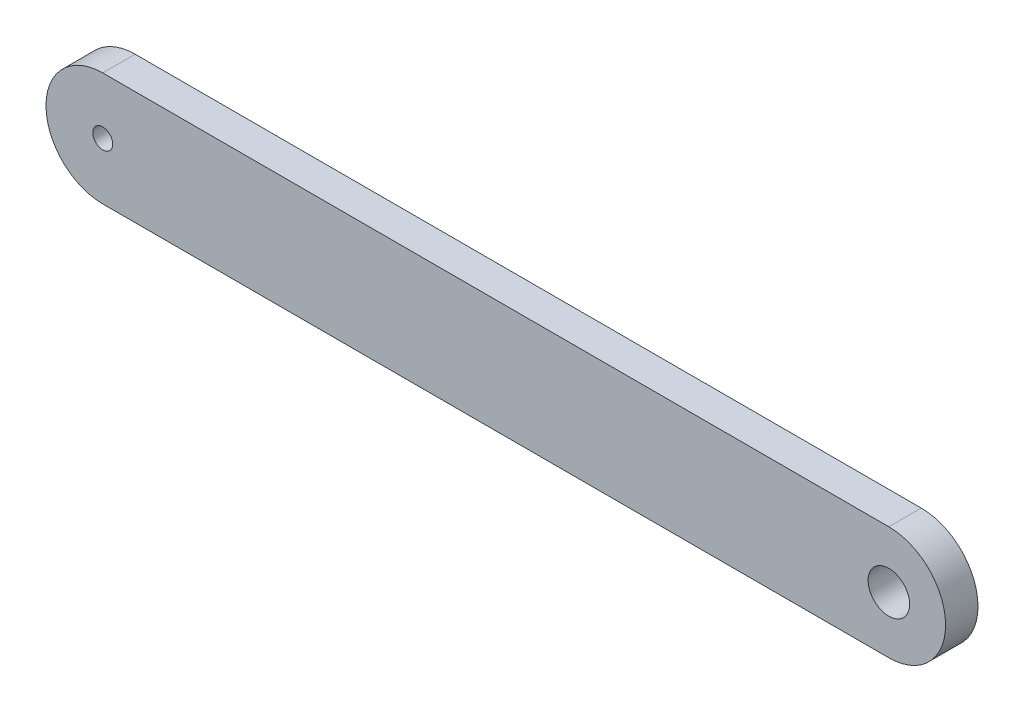
SolidWorks part; units mm, degrees
ref_plane "Front Plane" through (0, 0, 0) normal (0, 0, 1) x (1, 0, 0)
ref_plane "Top Plane" through (0, 0, 0) normal (0, 1, 0) x (1, 0, 0)
ref_plane "Right Plane" through (0, 0, 0) normal (1, 0, 0) x (0, 0, -1)
sketch "Sketch1" plane through (0, 0, 0) normal (0, 0, 1) x (1, 0, 0)
  line L0 (0, 8.89) -> (123.19, 8.89)
  line L1 (123.19, -8.89) -> (0, -8.89)
  arc A0 (0, 8.89) -> (0, -8.89) centre (0, 0) ccw
  arc A1 (123.19, 8.89) -> (123.19, -8.89) centre (123.19, 0) cw
  dimension "D1" = 17.78
  dimension "D2" = 123.19
extrude "Boss-Extrude1" add sketch "Sketch1" along normal blind 5.08
sketch "Sketch2" plane through (0, 0, 0) normal (0, 0, -1) x (-1, 0, 0)
  circle A0 centre (-123.19, 0) radius 3.2512
  dimension "D1" = 6.5024
sketch "Sketch4" plane through (0, 0, 0) normal (0, 0, -1) x (-1, 0, 0)
  line L3 (-5.6004, 4.064) -> (-16.6373, 2.8938)
  line L5 (-16.6337, -2.8942) -> (-5.3492, -4.0764)
  line L6 (5.3492, -4.0764) -> (16.6337, -2.8942)
  line L7 (16.6337, 2.8942) -> (5.3492, 4.0764)
  arc A9 (4.0773, 4.6338) -> (-4.0773, 4.6338) centre (0, 0) ccw
  arc A12 (-5.6004, 4.064) -> (-4.0773, 4.6338) centre (-5.5874, 6.35) ccw
  arc A13 (-16.6373, 2.8938) -> (-16.6337, -2.8942) centre (-16.3304, 0) ccw
  arc A14 (-5.3492, -4.0764) -> (-4.0773, -4.6338) centre (-5.5874, -6.35) cw
  arc A15 (-4.0773, -4.6338) -> (4.0773, -4.6338) centre (0, 0) ccw
  arc A16 (4.0773, -4.6338) -> (5.3492, -4.0764) centre (5.5874, -6.35) cw
  arc A17 (16.6337, -2.8942) -> (16.6337, 2.8942) centre (16.3304, 0) ccw
  arc A18 (5.3492, 4.0764) -> (4.0773, 4.6338) centre (5.5874, 6.35) cw
extrude "Cut-Extrude1" cut sketch "Sketch4" against normal blind 2.54
sketch "Sketch5" plane through (0, 0, 5.08) normal (0, 0, 1) x (1, 0, 0)
  circle A0 centre (0, 0) radius 1.5621
  dimension "D1" = 3.1242
extrude "Cut-Extrude2" cut sketch "Sketch5" against normal through all
extrude "Cut-Extrude3" cut sketch "Sketch2" against normal through all contours A0
